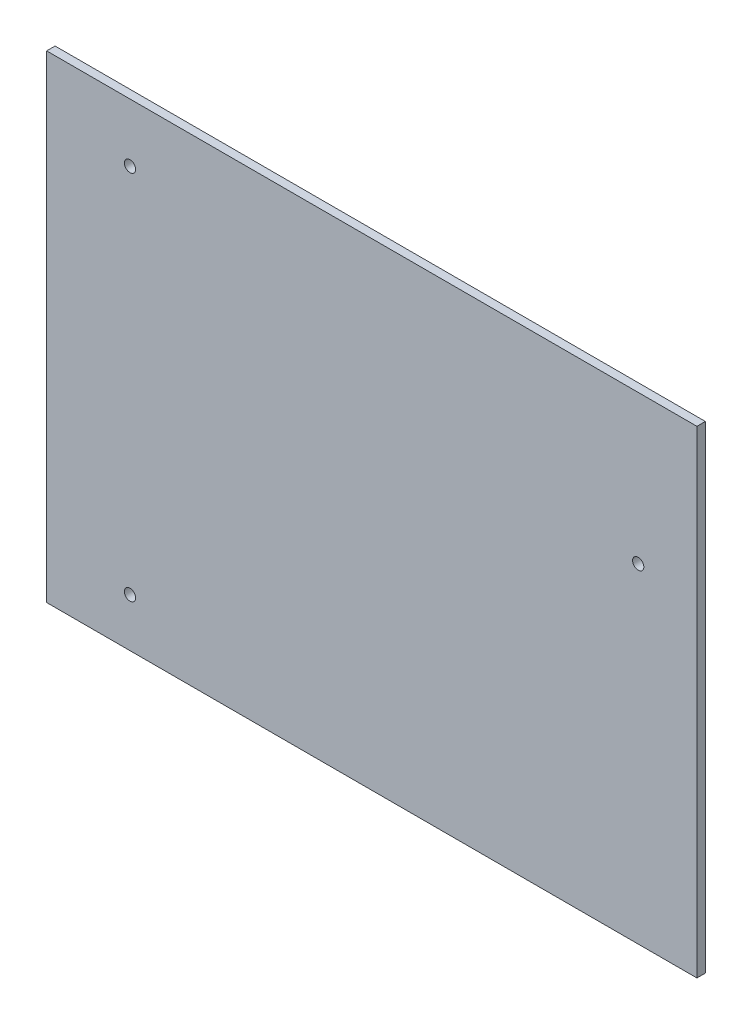
SolidWorks part; units mm, degrees
ref_plane "Front Plane" through (0, 0, 0) normal (0, 0, 1) x (1, 0, 0)
ref_plane "Top Plane" through (0, 0, 0) normal (0, 1, 0) x (1, 0, 0)
ref_plane "Right Plane" through (0, 0, 0) normal (1, 0, 0) x (0, 0, -1)
sketch "Sketch2" plane through (0, 0, 0) normal (0, 0, 1) x (1, 0, 0)
  line L0 (35.2798, 164.9086) -> (35.2798, 32.8769)
  line L1 (35.2798, 32.8769) -> (216.0682, 132.8104)
  line L2 (35.2798, 164.9086) -> (216.0682, 132.8104)
  dimension "D1" = 39
sketch "Sketch5" plane through (0, 0, 0) normal (0, 0, 1) x (1, 0, 0)
  line L1 (5.6212, 185.5975) -> (236.961, 185.5975)
  line L2 (5.6212, 185.5975) -> (5.6212, 15.6259)
  line L3 (5.6212, 15.6259) -> (236.961, 15.6259)
  line L4 (236.961, 185.5975) -> (236.961, 15.6259)
  circle A0 centre (35.2798, 164.9086) radius 2
  circle A1 centre (216.0682, 132.8104) radius 2
  circle A2 centre (35.2798, 32.8769) radius 2
  dimension "D1" = 4
  dimension "D2" = 4
  dimension "D3" = 4
extrude "Boss-Extrude1" add sketch "Sketch5" along normal blind 3 contours L2 L3 L4 L1 | A2 | A1 | A0
